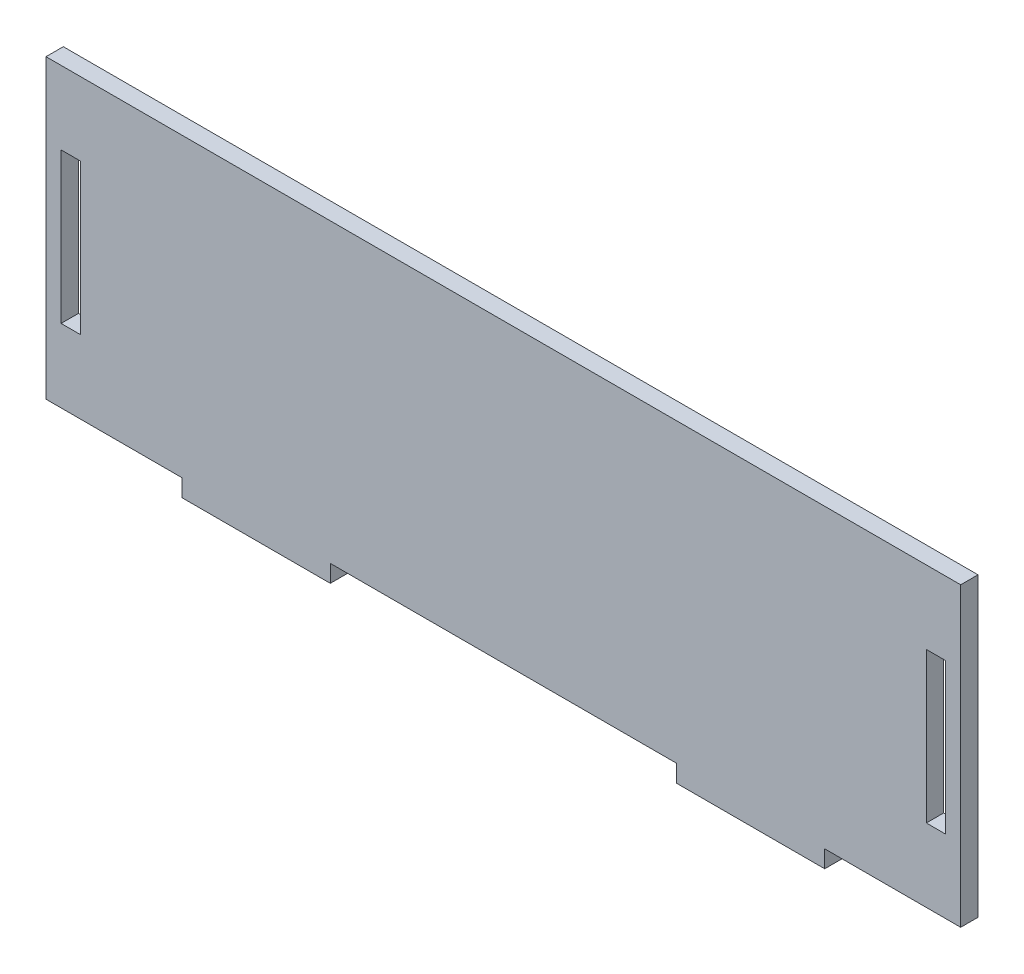
SolidWorks part; units mm, degrees
ref_plane "Спереди" through (0, 0, 0) normal (0, 0, 1) x (1, 0, 0)
ref_plane "Сверху" through (0, 0, 0) normal (0, 1, 0) x (1, 0, 0)
ref_plane "Справа" through (0, 0, 0) normal (1, 0, 0) x (0, 0, -1)
sketch "Эскиз1" plane through (0, 0, 0) normal (0, 0, 1) x (1, 0, 0)
  line L0 (92.5, 0) -> (92.5, 60) construction
  line L1 (0, 0) -> (185, 0)
  line L2 (0, 0) -> (0, 60)
  line L3 (0, 60) -> (185, 60)
  line L4 (185, 0) -> (185, 60)
  line L5 (27.5, 0) -> (57.5, 0)
  line L6 (27.5, 0) -> (27.5, -3.5)
  line L7 (27.5, -3.5) -> (57.5, -3.5)
  line L8 (57.5, 0) -> (57.5, -3.5)
  line L9 (42.5, -3.5) -> (42.5, 0) construction
  line L10 (157.5, -3.5) -> (127.5, -3.5)
  line L11 (127.5, 0) -> (127.5, -3.5)
  line L12 (157.5, 0) -> (127.5, 0)
  line L13 (157.5, 0) -> (157.5, -3.5)
  line L14 (0, 30) -> (5, 30) construction
  line L15 (181.95, 14.8) -> (178.05, 14.8)
  line L16 (3.05, 45.2) -> (6.95, 45.2)
  line L17 (3.05, 45.2) -> (3.05, 14.8)
  line L18 (3.05, 14.8) -> (6.95, 14.8)
  line L19 (6.95, 45.2) -> (6.95, 14.8)
  line L20 (3.05, 45.2) -> (6.95, 14.8) construction
  line L21 (3.05, 14.8) -> (6.95, 45.2) construction
  line L22 (178.05, 45.2) -> (178.05, 14.8)
  line L23 (181.95, 45.2) -> (178.05, 45.2)
  line L24 (181.95, 45.2) -> (181.95, 14.8)
  dimension "D1" = 185
  dimension "D2" = 60
  dimension "D3" = 30
  dimension "D4" = 3.5
  dimension "D5" = 50
  dimension "D6" = 30.4
  dimension "D7" = 3.9
  dimension "D8" = 5
extrude "Бобышка-Вытянуть1" add sketch "Эскиз1" along normal blind 3.5 contours L1 L4 L3 L2 | L8 L1 L6 L7 | L13 L1 L11 L10
